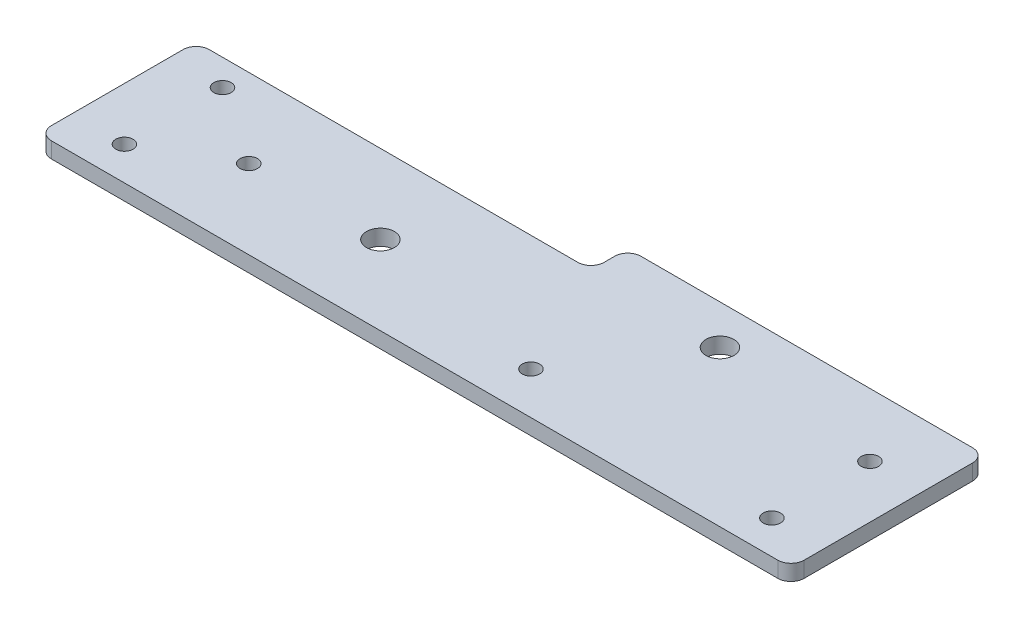
SolidWorks part; units mm, degrees
material "Thornel Mat VMA"
ref_plane "前视基准面" through (0, 0, 0) normal (0, 0, 1) x (1, 0, 0)
ref_plane "上视基准面" through (0, 0, 0) normal (0, 1, 0) x (1, 0, 0)
ref_plane "右视基准面" through (0, 0, 0) normal (1, 0, 0) x (0, 0, -1)
sketch "草图1" plane through (0, 0, 0) normal (0, 1, 0) x (1, 0, 0)
  line L0 (0, 0) -> (143, 0)
  line L5 (143, 0) -> (143, 37)
  line L6 (143, 37) -> (75, 37)
  line L7 (75, 37) -> (75, 30)
  line L8 (75, 30) -> (0, 30)
  line L9 (0, 30) -> (0, 0)
  line L10 (10, 30) -> (10, 0) construction
  line L11 (71.5, 0) -> (71.5, 30) construction
  line L13 (0, 15) -> (143, 15) construction
  circle A0 centre (10, 25) radius 1.65
  circle A1 centre (10, 6.37) radius 1.65
  circle A4 centre (50, 15) radius 2.65
  circle A5 centre (25, 15) radius 1.65
  circle A6 centre (100, 29.5) radius 2.65
  circle A7 centre (85.6, 8) radius 1.65
  circle A8 centre (133, 25) radius 1.65
  circle A9 centre (133, 6.37) radius 1.65
  dimension "D5" = 5
  dimension "D6" = 18.63
  dimension "D7" = 3.3
  dimension "D8" = 3.3
  dimension "D10" = 15
  dimension "D11" = 50
  dimension "D12" = 25
  dimension "D13" = 5.3
  dimension "D14" = 3.3
  dimension "D15" = 43
  dimension "D16" = 7.5
  dimension "D17" = 5.3
  dimension "D18" = 29
  dimension "D19" = 57.4
  dimension "D20" = 3.3
  dimension "D21" = 3.3
  dimension "D22" = 10
  dimension "D23" = 12
  dimension "D24" = 18.63
  dimension "D25" = 10
  dimension "D26" = 3.3
  dimension "D1" = 7
  dimension "D2" = 75
  dimension "D3" = 143
  dimension "D4" = 30
  dimension "D9" = 10
extrude "凸台-拉伸1" add sketch "草图1" along normal blind 3
fillet "圆角1" radius 2.5 6 edges at (0, 1.5, 0) (143, 1.5, 0) (143, 1.5, -37) (0, 1.5, -30) (75, 1.5, -37) (75, 1.5, -30)
